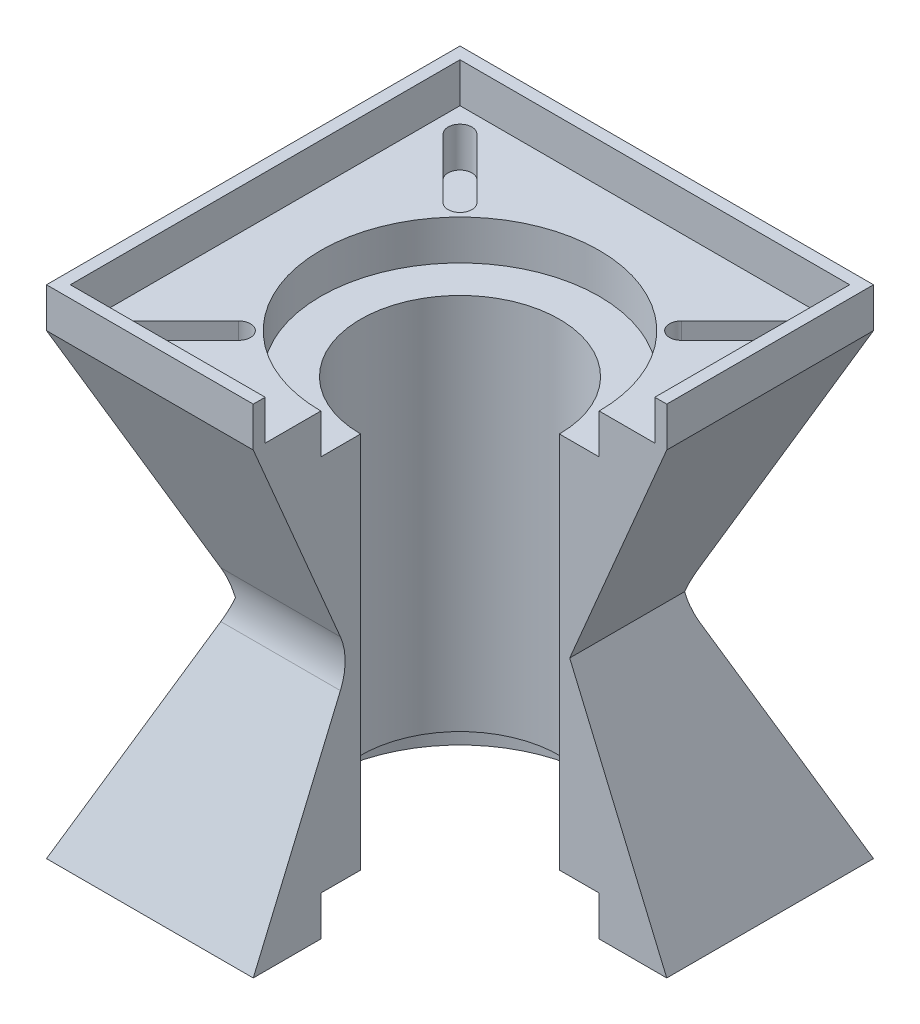
SolidWorks part; units mm, degrees
material "Cast Stainless Steel"
ref_plane "Front Plane" through (0, 0, 0) normal (0, 0, 1) x (1, 0, 0)
ref_plane "Top Plane" through (0, 0, 0) normal (0, 1, 0) x (1, 0, 0)
ref_plane "Right Plane" through (0, 0, 0) normal (1, 0, 0) x (0, 0, -1)
sketch "Sketch1" plane through (0, 0, 0) normal (0, 1, 0) x (1, 0, 0)
  line L1 (52, 52) -> (-52, 52)
  line L2 (52, 52) -> (52, -52)
  line L3 (52, -52) -> (-52, -52)
  line L4 (-52, 52) -> (-52, -52)
  line L5 (52, 52) -> (-52, -52) construction
  line L6 (52, -52) -> (-52, 52) construction
  point P0 (0, 0)
  dimension "D1" = 104
  dimension "D2" = 104
extrude "Boss-Extrude1" add sketch "Sketch1" along normal blind 115
sketch "Sketch2" plane through (52, 0, 0) normal (1, 0, 0) x (0, 0, -1)
  line L0 (-27.5927, 57.5) -> (52, 57.5) construction
  line L2 (52, 115) -> (52, 0) construction
  line L3 (-52, 115) -> (-52, 0)
  line L5 (-27.5927, 57.5) -> (-52, 115)
  line L6 (0, 115) -> (0, 0) construction
  line L7 (-52, 115) -> (52, 115) construction
  line L8 (-27.5927, 57.5) -> (-52, 0)
  line L9 (52, 115) -> (52, 0)
  line L10 (27.5927, 57.5) -> (52, 0)
  line L11 (27.5927, 57.5) -> (52, 115)
  dimension "D1" = 23
extrude "Cut-Extrude1" cut sketch "Sketch2" against normal through all
sketch "Sketch3" plane through (0, 0, 0) normal (0, 0, 1) x (1, 0, 0)
  line L0 (0, 115) -> (0, 0) construction
  line L1 (-52, 115) -> (52, 115) construction
  line L2 (-27.5927, 57.5) -> (52, 57.5) construction
  line L3 (-52, 115) -> (-27.5927, 57.5)
  line L5 (-52, 0) -> (-52, 115)
  line L6 (-52, 0) -> (-27.5927, 57.5)
  line L7 (52, 0) -> (27.5927, 57.5)
  line L8 (52, 115) -> (27.5927, 57.5)
  line L9 (52, 0) -> (52, 115)
  dimension "D1" = 23
extrude "Cut-Extrude2" cut sketch "Sketch3" against normal mid plane 115
sketch "Sketch4" plane through (0, 115, 0) normal (0, 1, 0) x (1, 0, 0)
  circle A0 centre (0, 0) radius 25
  dimension "D1" = 50
extrude "Cut-Extrude3" cut sketch "Sketch4" against normal through all
sketch "Sketch5" plane through (0, 115, 0) normal (0, 1, 0) x (1, 0, 0)
  circle A0 centre (0, 0) radius 35
  dimension "D1" = 70
extrude "Cut-Extrude4" cut sketch "Sketch5" against normal blind 10
sketch "Sketch6" plane through (0, 0, 0) normal (0, -1, 0) x (1, 0, 0)
  circle A0 centre (0, 0) radius 35
  dimension "D1" = 70
extrude "Cut-Extrude5" cut sketch "Sketch6" against normal blind 10
sketch "Sketch7" plane through (0, 115, 0) normal (0, 1, 0) x (1, 0, 0)
  line L0 (52, -52) -> (52, 52) construction
  line L1 (0, 0) -> (52, 0)
  line L2 (0, 0) -> (0, -52)
  line L3 (0, -52) -> (52, -52)
  line L4 (52, 0) -> (52, -52)
extrude "Cut-Extrude6" cut sketch "Sketch7" against normal through all
fillet "Fillet2" radius 15 1 edges at (0, 57.5, -27.5927)
fillet "Fillet3" radius 15 1 edges at (-13.7963, 57.5, 27.5927)
sketch "Sketch8" plane through (0, 115, 0) normal (0, 1, 0) x (1, 0, 0)
  line L4 (-49, 49) -> (49, 49)
  line L10 (-52, 52) -> (-52, -52)
  line L12 (49, 49) -> (49, 0)
  line L14 (49, 0) -> (52, 0)
  line L15 (52, 0) -> (52, 52)
  line L16 (52, 0) -> (52, 52) construction
  line L17 (52, 52) -> (-52, 52)
  line L19 (-52, -52) -> (0, -52) construction
  line L20 (-49, -49) -> (-49, 49)
  line L21 (-49, -49) -> (0, -49)
  line L22 (-52, -52) -> (0, -52)
  line L23 (0, -52) -> (0, -49)
  dimension "D1" = 3
  dimension "D2" = 3
  dimension "D3" = 3
  dimension "D4" = 3
extrude "Boss-Extrude2" add sketch "Sketch8" along normal blind 10
sketch "Sketch9" plane through (0, 115, 0) normal (0, 1, 0) x (1, 0, 0)
  line L1 (0, 0) -> (0, -52) construction
  line L2 (-42.8553, 42.8553) -> (-27.8553, 27.8553) construction
  line L3 (-40.734, 44.9767) -> (-25.734, 29.9767)
  line L4 (-44.9767, 40.734) -> (-29.9767, 25.734)
  line L5 (42.8553, 42.8553) -> (27.8553, 27.8553) construction
  line L6 (44.9767, 40.734) -> (29.9767, 25.734)
  line L7 (40.734, 44.9767) -> (25.734, 29.9767)
  line L11 (-42.8553, -42.8553) -> (-27.8553, -27.8553) construction
  line L12 (-44.9767, -40.734) -> (-29.9767, -25.734)
  line L13 (-40.734, -44.9767) -> (-25.734, -29.9767)
  line L17 (0, 0) -> (-42.8553, 42.8553) construction
  line L24 (42.8553, -42.8553) -> (27.8553, -27.8553) construction
  line L25 (40.734, -44.9767) -> (25.734, -29.9767)
  line L26 (44.9767, -40.734) -> (29.9767, -25.734)
  line L27 (42.8553, -42.8553) -> (27.8553, -27.8553) construction
  line L28 (40.734, -44.9767) -> (25.734, -29.9767)
  line L29 (44.9767, -40.734) -> (29.9767, -25.734)
  arc A0 (37.413, 33.1703) -> (0, -50) centre (0, 0) ccw construction
  arc A1 (-40.734, 44.9767) -> (-44.9767, 40.734) centre (-42.8553, 42.8553) ccw
  arc A2 (-29.9767, 25.734) -> (-25.734, 29.9767) centre (-27.8553, 27.8553) ccw
  arc A3 (44.9767, 40.734) -> (40.734, 44.9767) centre (42.8553, 42.8553) ccw
  arc A4 (25.734, 29.9767) -> (29.9767, 25.734) centre (27.8553, 27.8553) ccw
  arc A7 (-44.9767, -40.734) -> (-40.734, -44.9767) centre (-42.8553, -42.8553) ccw
  arc A8 (-25.734, -29.9767) -> (-29.9767, -25.734) centre (-27.8553, -27.8553) ccw
  arc A17 (40.734, -44.9767) -> (44.9767, -40.734) centre (42.8553, -42.8553) ccw
  arc A18 (29.9767, -25.734) -> (25.734, -29.9767) centre (27.8553, -27.8553) ccw
  point P3 (0, 0)
  point P4 (0, 0)
  point P9 (-35.3553, 35.3553)
  point P16 (35.3553, -35.3553)
  point P19 (35.3553, 35.3553)
  point P33 (-35.3553, -35.3553)
  point P38 (0, 0)
  point P49 (35.3553, -35.3553)
  point P56 (35.3553, -35.3553)
  point P63 (35.3553, -35.3553)
  point P70 (35.3553, -35.3553)
  dimension "D2" = 100
  dimension "D3" = 15
  dimension "D4" = 3
  dimension "D5" = 4
extrude "Cut-Extrude7" cut sketch "Sketch9" against normal blind 10
equation "\"a\"= 115mm"
equation "\"b\"= 104mm"
equation "\"c\"= 23mm"
